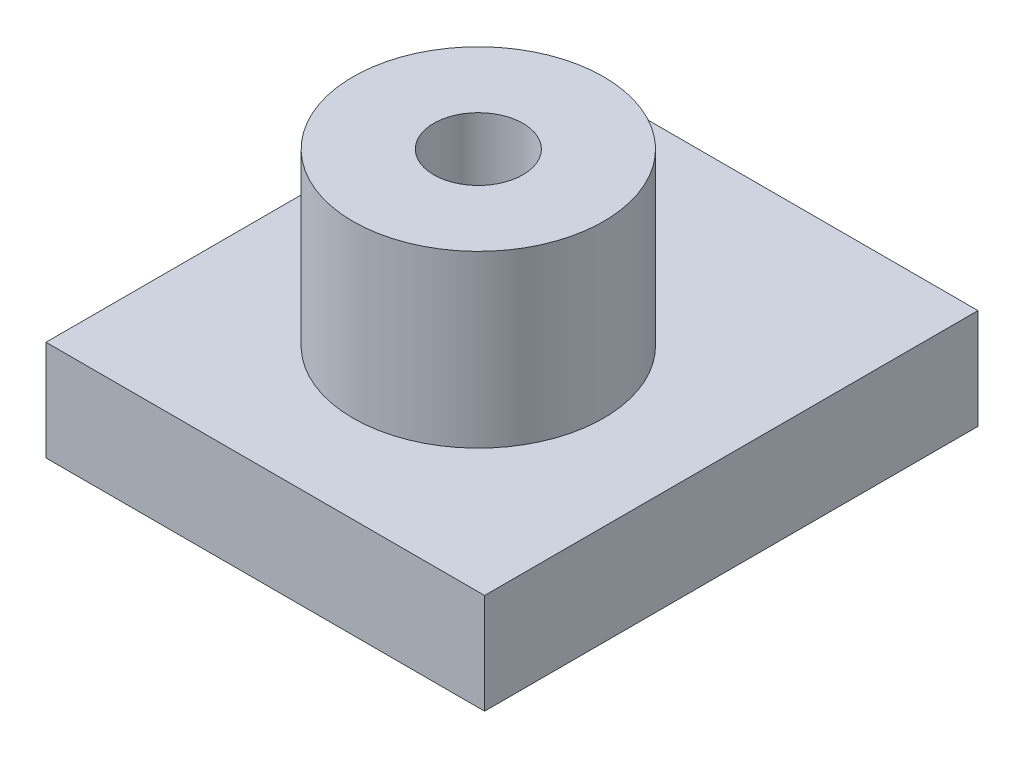
SolidWorks part; units mm, degrees
material "1060 Alloy"
ref_plane "Front Plane" through (0, 0, 0) normal (0, 0, 1) x (1, 0, 0)
ref_plane "Top Plane" through (0, 0, 0) normal (0, 1, 0) x (1, 0, 0)
ref_plane "Right Plane" through (0, 0, 0) normal (1, 0, 0) x (0, 0, -1)
sketch "Sketch1" plane through (0, 0, 0) normal (0, 1, 0) x (1, 0, 0)
  line L0 (0, 10.631) -> (0, 23.1323) construction
  line L1 (-5.5563, 23.1323) -> (5.5562, 23.1323)
  line L2 (-5.5563, 23.1323) -> (-5.5562, 10.631)
  line L3 (-5.5562, 10.631) -> (5.5562, 10.631)
  line L4 (5.5562, 23.1323) -> (5.5562, 10.631)
  line L5 (-68.2625, 10.631) -> (7.9375, 10.631) construction
  point P0 (0, 0)
  dimension "D1" = 11.1125
extrude "Boss-Extrude1" add sketch "Sketch1" along normal blind 2.54
sketch "Sketch2" plane through (0, 2.54, 0) normal (0, 1, 0) x (1, 0, 0)
  line L0 (0, 23.1323) -> (0, 10.631) construction
  line L1 (5.5562, 23.1323) -> (-5.5563, 23.1323) construction
  line L2 (-5.5562, 10.631) -> (5.5562, 10.631) construction
  circle A0 centre (0, 16.0285) radius 3.175
  circle A1 centre (0, 16.0285) radius 1.5875 construction
  dimension "D1" = 6.35
extrude "Boss-Extrude2" add sketch "Sketch2" along normal blind 4.318
hole_wizard "#4-40 Tapped Hole1" positions "Sketch4" profile "Sketch3" tap size "#4-40" standard "Ansi Inch" end condition through all
sketch "Sketch4" plane through (0, 6.858, 0) normal (0, 1, 0) x (-1, 0, 0)
  point P0 (0, -16.0285)
cosmetic thread "Hole Thread1" parameters "D2"=2.8448
sketch "Sketch3" plane through (0, 6.858, -16.0285) normal (1, 0, 0) x (0, 0, 1)
  line L0 (0, 0) -> (0, 6.858)
  line L1 (0, 6.858) -> (1.1303, 6.858)
  line L2 (1.1303, 6.858) -> (1.1303, 0)
  line L5 (1.1303, 0) -> (0, 0)
  line L11 (0, -6.35) -> (0, 107.95) construction
  dimension "Thru Tap Drill Dia." = 2.2606
  dimension "Thru Tap Drill Depth" = 6.858
